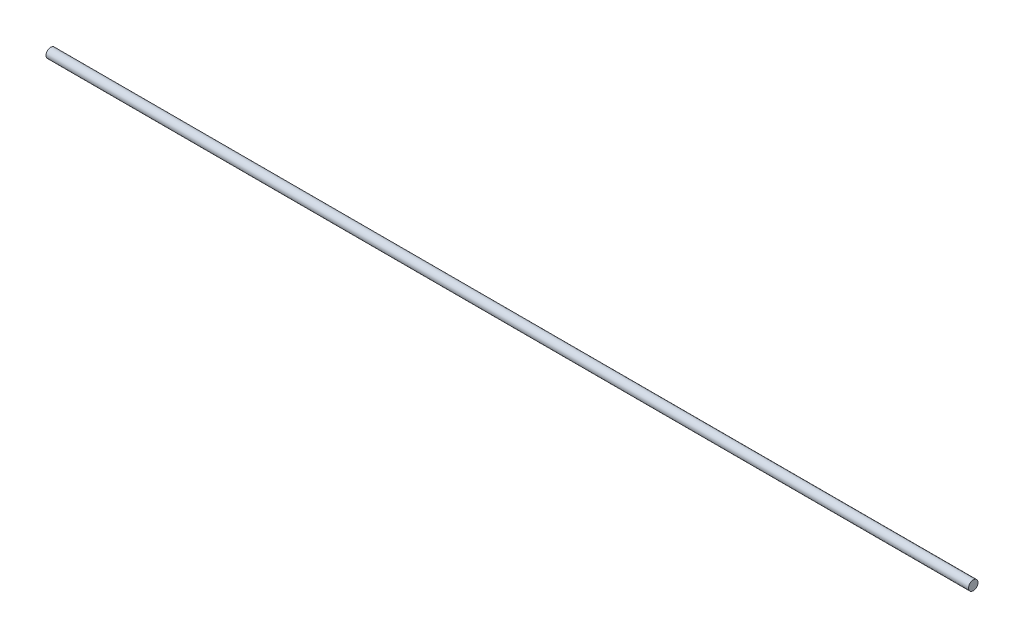
SolidWorks part; units mm, degrees
material "Galvanized Steel"
ref_plane "Front Plane" through (0, 0, 0) normal (0, 0, 1) x (1, 0, 0)
ref_plane "Top Plane" through (0, 0, 0) normal (0, 1, 0) x (1, 0, 0)
ref_plane "Right Plane" through (0, 0, 0) normal (1, 0, 0) x (0, 0, -1)
sketch "Sketch1" plane through (0, 0, 0) normal (1, 0, 0) x (0, 0, -1)
  circle A0 centre (0, 0) radius 6.35
  dimension "D1" = 12.7
extrude "Boss-Extrude1" add sketch "Sketch1" along normal mid plane 1236.6625
